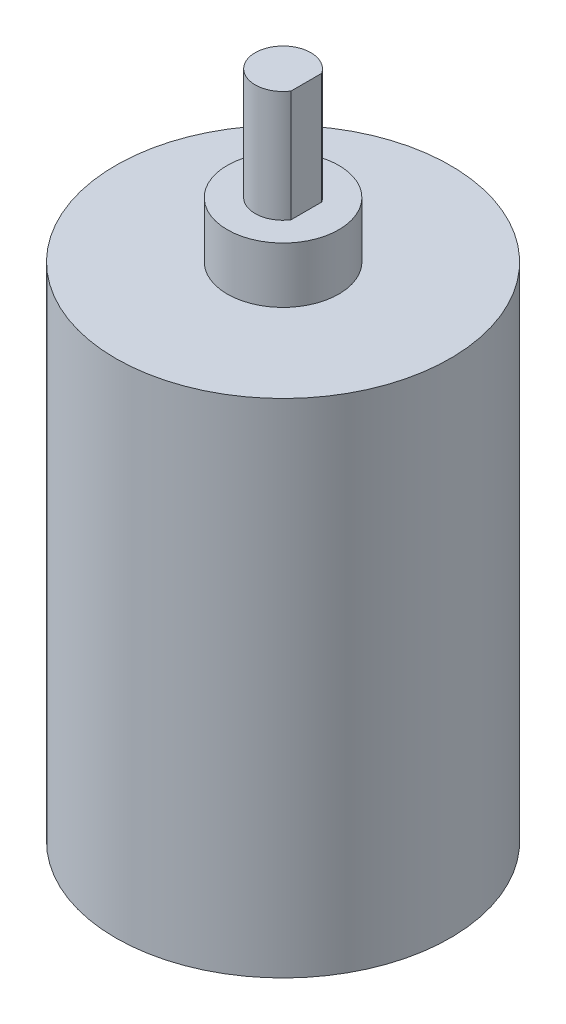
SolidWorks part; units mm, degrees
ref_plane "Front Plane" through (0, 0, 0) normal (0, 0, 1) x (1, 0, 0)
ref_plane "Top Plane" through (0, 0, 0) normal (0, 1, 0) x (1, 0, 0)
ref_plane "Right Plane" through (0, 0, 0) normal (1, 0, 0) x (0, 0, -1)
sketch "Sketch1" plane through (0, 0, 0) normal (0, 1, 0) x (1, 0, 0)
  circle A0 centre (0, 0) radius 19.05
  dimension "D1" = 38.1
extrude "Boss-Extrude1" add sketch "Sketch1" along normal blind 57.15
sketch "Sketch2" plane through (0, 57.15, 0) normal (0, 1, 0) x (1, 0, 0)
  circle A0 centre (0, 0) radius 6.35
  circle A1 centre (0, 0) radius 19.05 construction
  dimension "D1" = 12.7
extrude "Boss-Extrude2" add sketch "Sketch2" along normal blind 6.35
sketch "Sketch3" plane through (0, 63.5, 0) normal (0, 1, 0) x (1, 0, 0)
  circle A0 centre (0, 0) radius 3.175
  dimension "D1" = 6.35
extrude "Boss-Extrude3" add sketch "Sketch3" along normal blind 12.7
sketch "Sketch4" plane through (0, 76.2, 0) normal (0, 1, 0) x (1, 0, 0)
  line L0 (2.6488, 1.7506) -> (2.6488, -1.7506)
  circle A0 centre (0, 0) radius 3.175 construction
  circle A1 centre (0, 0) radius 3.175 construction
  arc A2 (2.6488, 1.7506) -> (2.6488, -1.7506) centre (0, 0) cw
extrude "Cut-Extrude1" cut sketch "Sketch4" against normal up to surface (12.7 mm away) up to face at (0, 63.5, 3.175)
